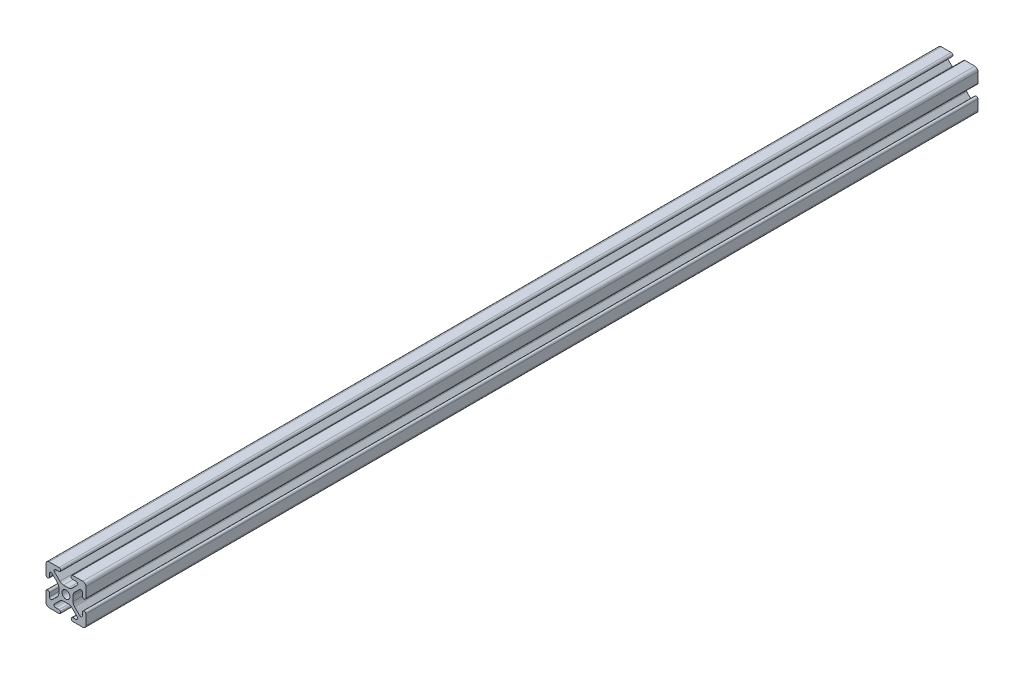
SolidWorks part; units mm, degrees
material "6005A-T61"
ref_plane "Front Plane" through (0, 0, 0) normal (0, 0, 1) x (1, 0, 0)
ref_plane "Top Plane" through (0, 0, 0) normal (0, 1, 0) x (1, 0, 0)
ref_plane "Right Plane" through (0, 0, 0) normal (1, 0, 0) x (0, 0, -1)
sketch "Sketch1" plane through (0, 0, 0) normal (0, 0, 1) x (1, 0, 0)
  line L0 (-8.6363, 7.1116) -> (-5.4322, 3.9121)
  line L1 (-4.455, 1.5554) -> (-4.455, -1.5554)
  line L2 (-5.4322, -3.9121) -> (-8.6363, -7.1116)
  line L3 (-10.36, -6.3969) -> (-10.36, -4.32)
  line L4 (-12.5, -4.32) -> (-12.5, -8.6518)
  line L5 (-12.5, -8.6518) -> (-12.5, -10.5371)
  line L6 (-10.5371, -12.5) -> (-8.4416, -12.5)
  line L7 (-8.4416, -12.5) -> (-4.3879, -12.5)
  line L8 (-4.3879, -10.36) -> (-6.42, -10.36)
  line L9 (-7.1337, -8.6353) -> (-3.7953, -5.3018)
  line L10 (-1.5554, -4.375) -> (1.5554, -4.375)
  line L11 (10.36, 4.32) -> (10.36, 6.3969)
  line L12 (12.5, 7.9913) -> (12.5, 4.32)
  line L13 (12.5, 10.5371) -> (12.5, 7.9913)
  line L14 (4.32, 12.5) -> (10.5371, 12.5)
  line L16 (6.42, 10.36) -> (4.32, 10.36)
  line L17 (3.7953, 5.3018) -> (7.1337, 8.6353)
  line L18 (7.1337, -8.6353) -> (3.7953, -5.3018)
  line L19 (4.3879, -10.36) -> (6.42, -10.36)
  line L20 (8.4416, -12.5) -> (4.3879, -12.5)
  line L21 (10.5371, -12.5) -> (8.4416, -12.5)
  line L22 (12.5, -8.6518) -> (12.5, -10.5371)
  line L23 (12.5, -4.32) -> (12.5, -8.6518)
  line L24 (10.36, -6.3969) -> (10.36, -4.32)
  line L25 (5.4322, -3.9121) -> (8.6363, -7.1116)
  line L26 (4.455, 1.5554) -> (4.455, -1.5554)
  line L27 (8.6363, 7.1116) -> (5.4322, 3.9121)
  line L28 (1.5554, 4.375) -> (-1.5554, 4.375)
  line L29 (-3.7953, 5.3018) -> (-7.1337, 8.6353)
  line L30 (-6.42, 10.36) -> (-4.32, 10.36)
  line L32 (-4.32, 12.5) -> (-10.5371, 12.5)
  line L33 (-12.5, 10.5371) -> (-12.5, 7.9913)
  line L34 (-12.5, 7.9913) -> (-12.5, 4.32)
  line L35 (-10.36, 4.32) -> (-10.36, 6.3969)
  line L36 (-15.7693, 0) -> (12.5, 0) construction
  line L37 (0, 13.9334) -> (0, -12.3541) construction
  circle A0 centre (0, 0) radius 2.5
  arc A1 (-8.6363, 7.1116) -> (-10.36, 6.3969) centre (-9.35, 6.3969) ccw
  arc A2 (-4.455, 1.5554) -> (-5.4322, 3.9121) centre (-7.7855, 1.5554) ccw
  arc A3 (-5.4322, -3.9121) -> (-4.455, -1.5554) centre (-7.7855, -1.5554) ccw
  arc A4 (-10.36, -6.3969) -> (-8.6363, -7.1116) centre (-9.35, -6.3969) ccw
  arc A5 (-10.36, -4.32) -> (-12.5, -4.32) centre (-11.43, -4.32) ccw
  arc A6 (-12.5, -10.5371) -> (-10.5371, -12.5) centre (-10.5371, -10.5371) ccw
  arc A7 (-4.3879, -12.5) -> (-4.3879, -10.36) centre (-4.3879, -11.43) ccw
  arc A8 (-7.1337, -8.6353) -> (-6.42, -10.36) centre (-6.42, -9.35) ccw
  arc A9 (-1.5554, -4.375) -> (-3.7953, -5.3018) centre (-1.5554, -7.545) ccw
  arc A10 (12.5, 4.32) -> (10.36, 4.32) centre (11.43, 4.32) cw
  arc A11 (10.5371, 12.5) -> (12.5, 10.5371) centre (10.5371, 10.5371) cw
  arc A12 (4.32, 10.36) -> (4.32, 12.5) centre (4.32, 11.43) cw
  arc A13 (6.42, 10.36) -> (7.1337, 8.6353) centre (6.42, 9.35) cw
  arc A14 (3.7953, 5.3018) -> (1.5554, 4.375) centre (1.5554, 7.545) cw
  arc A15 (1.5554, -4.375) -> (3.7953, -5.3018) centre (1.5554, -7.545) cw
  arc A16 (7.1337, -8.6353) -> (6.42, -10.36) centre (6.42, -9.35) cw
  arc A17 (4.3879, -12.5) -> (4.3879, -10.36) centre (4.3879, -11.43) cw
  arc A18 (12.5, -10.5371) -> (10.5371, -12.5) centre (10.5371, -10.5371) cw
  arc A19 (10.36, -4.32) -> (12.5, -4.32) centre (11.43, -4.32) cw
  arc A20 (10.36, -6.3969) -> (8.6363, -7.1116) centre (9.35, -6.3969) cw
  arc A21 (5.4322, -3.9121) -> (4.455, -1.5554) centre (7.7855, -1.5554) cw
  arc A22 (4.455, 1.5554) -> (5.4322, 3.9121) centre (7.7855, 1.5554) cw
  arc A23 (8.6363, 7.1116) -> (10.36, 6.3969) centre (9.35, 6.3969) cw
  arc A24 (-3.7953, 5.3018) -> (-1.5554, 4.375) centre (-1.5554, 7.545) ccw
  arc A25 (-6.42, 10.36) -> (-7.1337, 8.6353) centre (-6.42, 9.35) ccw
  arc A26 (-4.32, 10.36) -> (-4.32, 12.5) centre (-4.32, 11.43) ccw
  arc A27 (-10.5371, 12.5) -> (-12.5, 10.5371) centre (-10.5371, 10.5371) ccw
  arc A28 (-12.5, 4.32) -> (-10.36, 4.32) centre (-11.43, 4.32) ccw
  dimension "D4" = 14.86
  dimension "D5" = 2.14
  dimension "D6" = 6.5
  dimension "D7" = 8.75
  dimension "D8" = 1.01
  dimension "D9" = 3.17
  dimension "D14" = 5
  dimension "D1" = 25
  dimension "D2" = 8.91
  dimension "D3" = 12.5
  dimension "D12" = 2.14
extrude "Extrude1" add sketch "Sketch1" against normal blind 559.6
equation "\"WallThickness\"= 0.5cm"
equation "\"BottomPlateX\"= 3ft"
equation "\"BottomPlateZ\"= 2ft"
equation "\"BottomPlateHoleD\"=((\"ArmPlateX\")^2+(\"ArmPlateDepth\")^2)^.5+ 10mm"
equation "\"ActuatorPinD\"= 6.35mm"
equation "\"ActuatorPinL\"= 15cm"
equation "\"Box-X\"= 40cm"
equation "\"Box-Z\"= 20cm"
equation "\"Box-Y\"= 30cm"
equation "\"ArmPlateThickness\"= .125in"
equation "\"ArmPlateX\"= 18in"
equation "\"ArmPlateDepth\"= 7.1875in"
equation "\"DCMotor1D\"= 65mm"
equation "\"DCMotor1L\"= 215mm"
equation "\"DCMotor1ShaftL\"= 30mm"
equation "\"DCMotor2X\"= 68mm"
equation "\"DCMotor2D\"= 65mm"
equation "\"DCMotor2L\"= 208mm"
equation "\"DCMotor2ShaftL\"= 39mm"
equation "\"DCMotor2ShaftD\"= 15mm"
equation "\"BenchDepth\"= 5cm"
equation "\"BenchH\"= 10cm"
equation "\"BenchL\"= 15cm"
equation "\"PillowBlockW\"= 5cm"
equation "\"PillowBlockCenterH\"= \"DCMotor2X\"/2"
equation "\"EncoderRadius\"= 19mm"
equation "\"EncoderShaftL\"= 15mm"
equation "\"EncoderL\"= 33mm"
equation "\"EncoderHousingThickness\"= 7.5mm"
equation "\"TurntableID\"= 70mm"
equation "\"TurntableInner2*t\" = (\"TurntableOD\"-\"TurntableID\")*.25 - 1mm"
equation "\"TurntableInnerHoleRadius\"= \"TurntableID\"*.5 + \"TurntableInner2*t\"*.5"
equation "\"TurntableOD\"= 120mm"
equation "\"TurntableOuterHoleRadius\" = \"TurntableOD\"*.5 - ((\"TurntableOD\"-\"TurntableID\")*.25-.5mm)*.5"
equation "\"2525Height\" = 30cm"
equation "\"LENGTH@Extrude1\"=\"BottomPlateZ\"-50mm"
